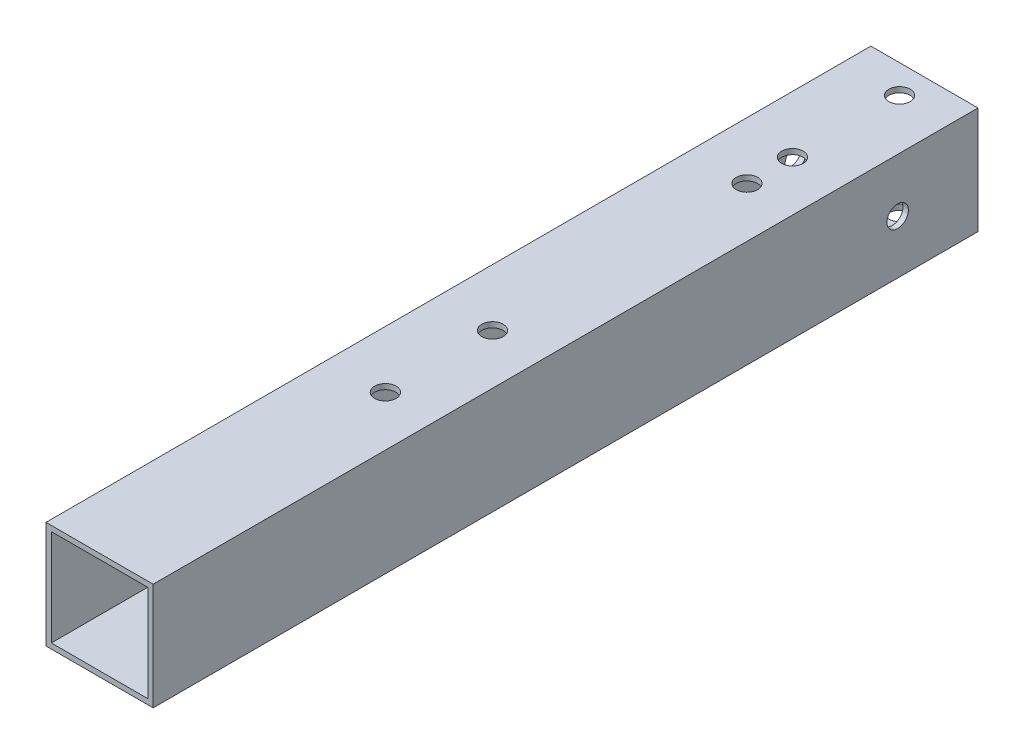
SolidWorks part; units mm, degrees
ref_plane "前视基准面" through (0, 0, 0) normal (0, 0, 1) x (1, 0, 0)
ref_plane "上视基准面" through (0, 0, 0) normal (0, 1, 0) x (1, 0, 0)
ref_plane "右视基准面" through (0, 0, 0) normal (1, 0, 0) x (0, 0, -1)
sketch "草图1" plane through (0, 0, 0) normal (0, 0, 1) x (1, 0, 0)
  line L1 (-10, 10) -> (10, 10)
  line L2 (-10, 10) -> (-10, -10)
  line L3 (-10, -10) -> (10, -10)
  line L4 (10, 10) -> (10, -10)
  line L5 (-10, 10) -> (10, -10) construction
  line L6 (-10, -10) -> (10, 10) construction
  line L7 (-9, 9) -> (9, 9)
  line L8 (-9, 9) -> (-9, -9)
  line L9 (-9, -9) -> (9, -9)
  line L10 (9, 9) -> (9, -9)
  line L11 (-9, 9) -> (9, -9) construction
  line L12 (-9, -9) -> (9, 9) construction
  point P0 (0, 0)
  point P5 (0, 0)
  dimension "D1" = 20
  dimension "D2" = 18
extrude "凸台-拉伸1" add sketch "草图1" along normal mid plane 167
sketch "草图3" plane through (0, 0, 0) normal (0, 1, 0) x (1, 0, 0)
  circle A0 centre (0.6459, -30.7887) radius 2 construction
  circle A1 centre (0.6459, -10.7887) radius 2 construction
  circle A2 centre (0.6459, 36.7113) radius 2 construction
  circle A3 centre (0.6459, 45.2113) radius 2 construction
  circle A4 centre (0.6459, 65.2113) radius 2 construction
  circle A5 centre (0.6459, -30.7887) radius 2
  circle A6 centre (0.6459, -10.7887) radius 2
  circle A7 centre (0.6459, 36.7113) radius 2
  circle A8 centre (0.6459, 45.2113) radius 2
  circle A9 centre (0.6459, 65.2113) radius 2
extrude "切除-拉伸2" cut sketch "草图3" against normal through all both and the other way through all
sketch "草图5" plane through (10, 0, 0) normal (1, 0, 0) x (0, 0, -1)
  line L1 (83.5, -10) -> (70.5, -10)
  line L2 (83.5, -10) -> (83.5, 10)
  line L3 (83.5, 10) -> (70.5, 10)
  line L4 (70.5, -10) -> (70.5, 10)
  line L5 (-83.5, 10) -> (83.5, 10) construction
  dimension "D1" = 20
  dimension "D2" = 13
extrude "切除-拉伸3" cut sketch "草图5" against normal through all
sketch "草图7" plane through (10, 0, 0) normal (1, 0, 0) x (0, 0, -1)
  line L0 (70.5, 10) -> (70.5, -10) construction
  circle A2 centre (55.5, 0) radius 2
  point P4 (0, 0)
  dimension "D1" = 4
  dimension "D2" = 15
extrude "切除-拉伸4" cut sketch "草图7" against normal through all
